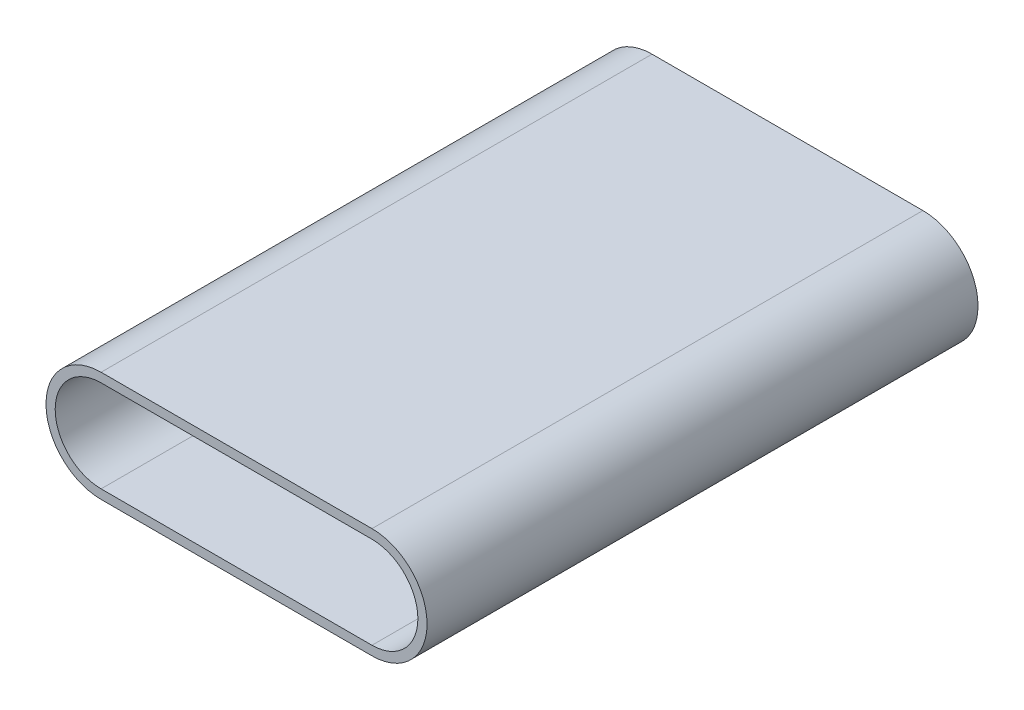
SolidWorks part; units mm, degrees
material "Chrome Stainless Steel"
ref_plane "Front Plane" through (0, 0, 0) normal (0, 0, 1) x (1, 0, 0)
ref_plane "Top Plane" through (0, 0, 0) normal (0, 1, 0) x (1, 0, 0)
ref_plane "Right Plane" through (0, 0, 0) normal (1, 0, 0) x (0, 0, -1)
sketch "USBCProfileS" plane through (0, 0, 0) normal (0, 0, 1) x (1, 0, 0)
  line L0 (-2.95, 0) -> (2.95, 0) construction
  line L1 (-2.95, 1.2) -> (2.95, 1.2)
  line L2 (-2.95, -1.2) -> (2.95, -1.2)
  line L3 (-2.95, 1) -> (2.95, 1)
  line L4 (-2.95, -1) -> (2.95, -1)
  arc A0 (-2.95, 1.2) -> (-2.95, -1.2) centre (-2.95, 0) ccw
  arc A1 (2.95, -1.2) -> (2.95, 1.2) centre (2.95, 0) ccw
  arc A2 (2.95, -1) -> (2.95, 1) centre (2.95, 0) ccw
  arc A3 (-2.95, 1) -> (-2.95, -1) centre (-2.95, 0) ccw
  point P2 (0, 0)
  point P8 (-4.15, 0)
  point P9 (4.15, 0)
  point P16 (-3.95, 0)
  point P17 (3.95, 0)
  dimension "Height" = 2.4
  dimension "Width" = 8.3
  dimension "RefHeight" = 2
  dimension "RefWidth" = 7.9
  dimension "WallThickness" = 0.2
extrude "USBCProfile" add sketch "USBCProfileS" along normal mid plane 12
